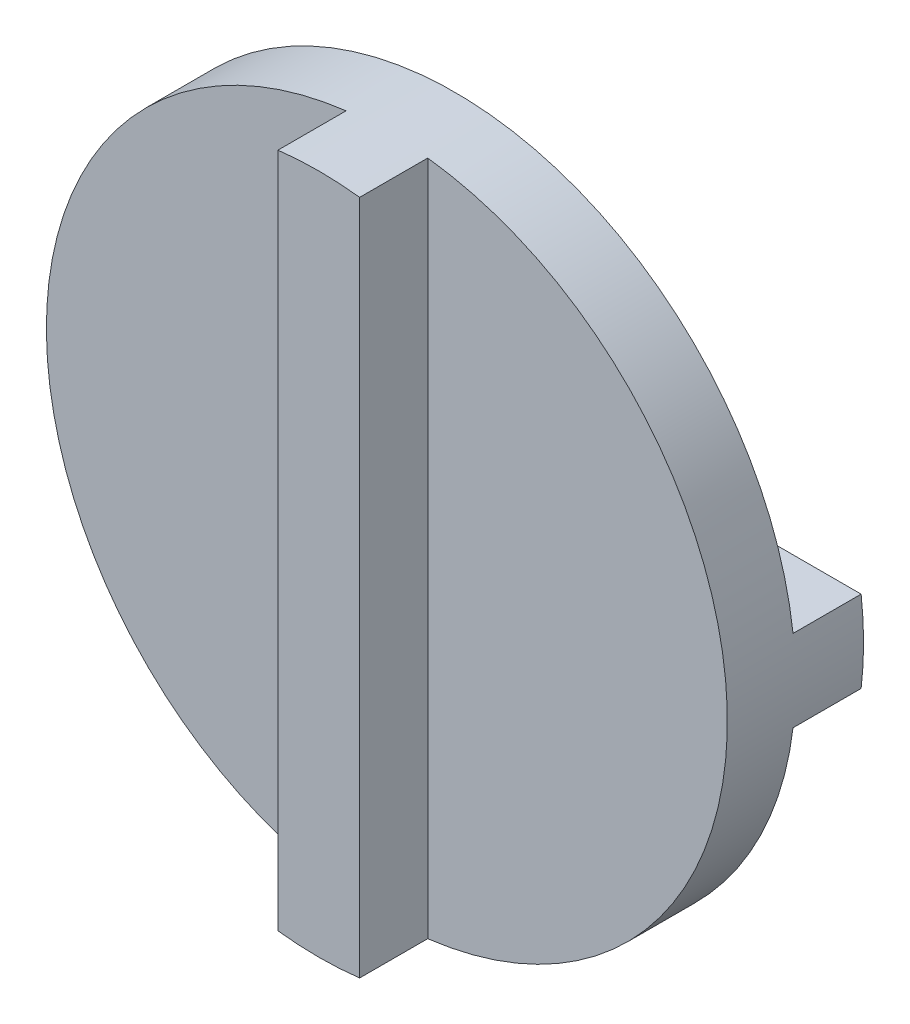
SolidWorks part; units mm, degrees
ref_plane "Front Plane" through (0, 0, 0) normal (0, 0, 1) x (1, 0, 0)
ref_plane "Top Plane" through (0, 0, 0) normal (0, 1, 0) x (1, 0, 0)
ref_plane "Right Plane" through (0, 0, 0) normal (1, 0, 0) x (0, 0, -1)
sketch "Sketch2" plane through (0, 0, 0) normal (0, 0, 1) x (1, 0, 0)
  circle A0 centre (0, 0) radius 50
  dimension "D1" = 100
extrude "Boss-Extrude1" add sketch "Sketch2" along normal blind 10
sketch "Sketch3" plane through (0, 0, 0) normal (0, 0, -1) x (-1, 0, 0)
  line L0 (-49.6387, 6) -> (49.6387, 6)
  line L1 (-49.6387, -6) -> (49.6387, -6)
  circle A0 centre (0, 0) radius 50 construction
  arc A1 (-49.6387, 6) -> (-49.6387, -6) centre (0, 0) ccw
  arc A2 (49.6387, -6) -> (49.6387, 6) centre (0, 0) ccw
  dimension "D1" = 12
extrude "Boss-Extrude2" add sketch "Sketch3" along normal blind 10
sketch "Sketch5" plane through (0, 0, 10) normal (0, 0, 1) x (1, 0, 0)
  line L0 (-6, 49.6387) -> (-6, -49.6387)
  line L1 (6, -49.6387) -> (6, 49.6387)
  circle A0 centre (0, 0) radius 50 construction
  arc A1 (-6, -49.6387) -> (6, -49.6387) centre (0, 0) ccw
  circle A2 centre (0, 0) radius 50
  arc A3 (6, 49.6387) -> (-6, 49.6387) centre (0, 0) ccw
  dimension "D1" = 12
  dimension "D2" = 0
extrude "Boss-Extrude3" add sketch "Sketch5" along normal blind 10
